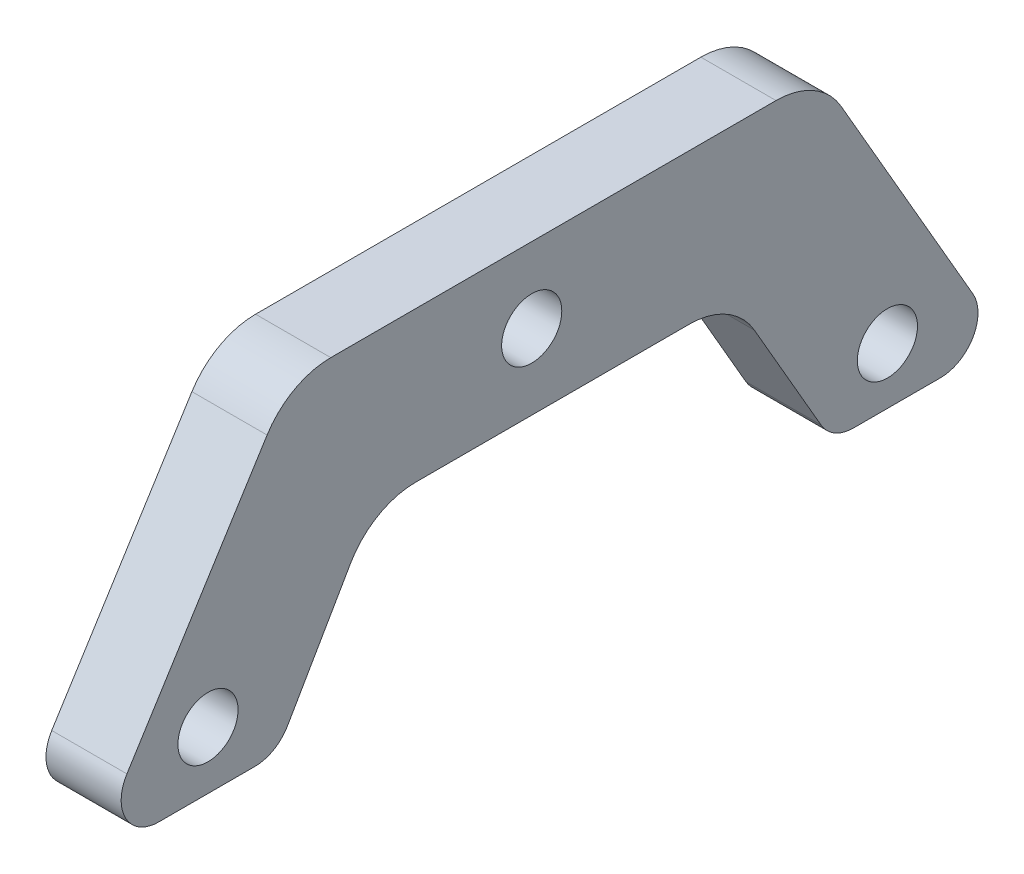
SolidWorks part; units mm, degrees
ref_plane "Front Plane" through (0, 0, 0) normal (0, 0, 1) x (1, 0, 0)
ref_plane "Top Plane" through (0, 0, 0) normal (0, 1, 0) x (1, 0, 0)
ref_plane "Right Plane" through (0, 0, 0) normal (1, 0, 0) x (0, 0, -1)
sketch "Sketch1" plane through (0, 0, 0) normal (1, 0, 0) x (0, 0, -1)
  line L0 (-139.2481, 30.6197) -> (-101.9552, 90.0444)
  line L1 (-85.0148, 99.4132) -> (33.4417, 99.4132)
  line L2 (50.7622, 89.4132) -> (85.8409, 28.6551)
  line L3 (77.1807, 13.6551) -> (54.0866, 13.6551)
  line L4 (45.4264, 18.6551) -> (27.6682, 49.4132)
  line L5 (10.3477, 59.4132) -> (-62.4069, 59.4132)
  line L6 (-79.7274, 49.4132) -> (-96.5336, 20.3041)
  line L7 (-105.1938, 15.3041) -> (-130.7779, 15.3041)
  arc A0 (33.4417, 99.4132) -> (50.7622, 89.4132) centre (33.4417, 79.4132) cw
  arc A1 (27.6682, 49.4132) -> (10.3477, 59.4132) centre (10.3477, 39.4132) ccw
  arc A2 (-62.4069, 59.4132) -> (-79.7274, 49.4132) centre (-62.4069, 39.4132) ccw
  arc A3 (-101.9552, 90.0444) -> (-85.0148, 99.4132) centre (-85.0148, 79.4132) cw
  arc A4 (85.8409, 28.6551) -> (77.1807, 13.6551) centre (77.1807, 23.6551) cw
  arc A5 (54.0866, 13.6551) -> (45.4264, 18.6551) centre (54.0866, 23.6551) cw
  arc A6 (-96.5336, 20.3041) -> (-105.1938, 15.3041) centre (-105.1938, 25.3041) cw
  arc A7 (-139.2481, 30.6197) -> (-130.7779, 15.3041) centre (-130.7779, 25.3041) ccw
  circle A8 centre (-31.5538, 79.4132) radius 8
  circle A9 centre (-117.6816, 30.6197) radius 8
  circle A10 centre (63.0734, 28.6551) radius 8
  point P14 (-73.9539, 59.4132)
  point P17 (-96.0757, 99.4132)
  point P26 (-148.8597, 15.3041)
  dimension "D7" = 20
  dimension "D8" = 10
  dimension "D9" = 16
  dimension "D1" = 40
  dimension "D2" = 40
  dimension "D3" = 120
  dimension "D4" = 120
  dimension "D5" = 40
  dimension "D6" = 99.3
extrude "Boss-Extrude1" add sketch "Sketch1" along normal blind 20
